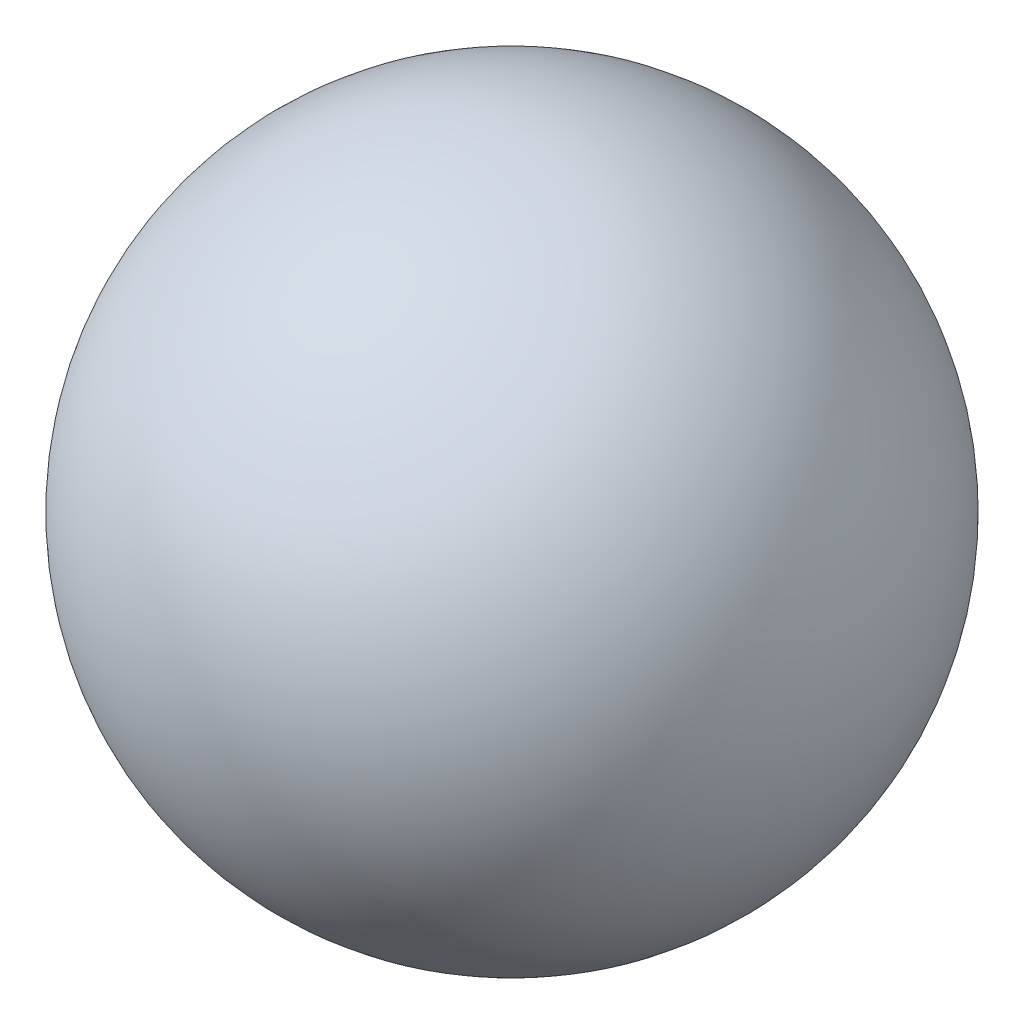
SolidWorks part; units mm, degrees
material "Plain Carbon Steel"
ref_plane "Front" through (0, 0, 0) normal (0, 0, 1) x (1, 0, 0)
ref_plane "Top" through (0, 0, 0) normal (0, 1, 0) x (1, 0, 0)
ref_plane "Right" through (0, 0, 0) normal (1, 0, 0) x (0, 0, -1)
sketch "Sketch1" plane through (0, 0, 0) normal (0, 0, 1) x (1, 0, 0)
  line L0 (0, -12.7) -> (0, 12.7)
  arc A0 (0, -12.7) -> (0, 12.7) centre (0, 0) ccw
  dimension "D1" = 25.4
revolve "Revolve1" add sketch "Sketch1" angle 360 about L0
